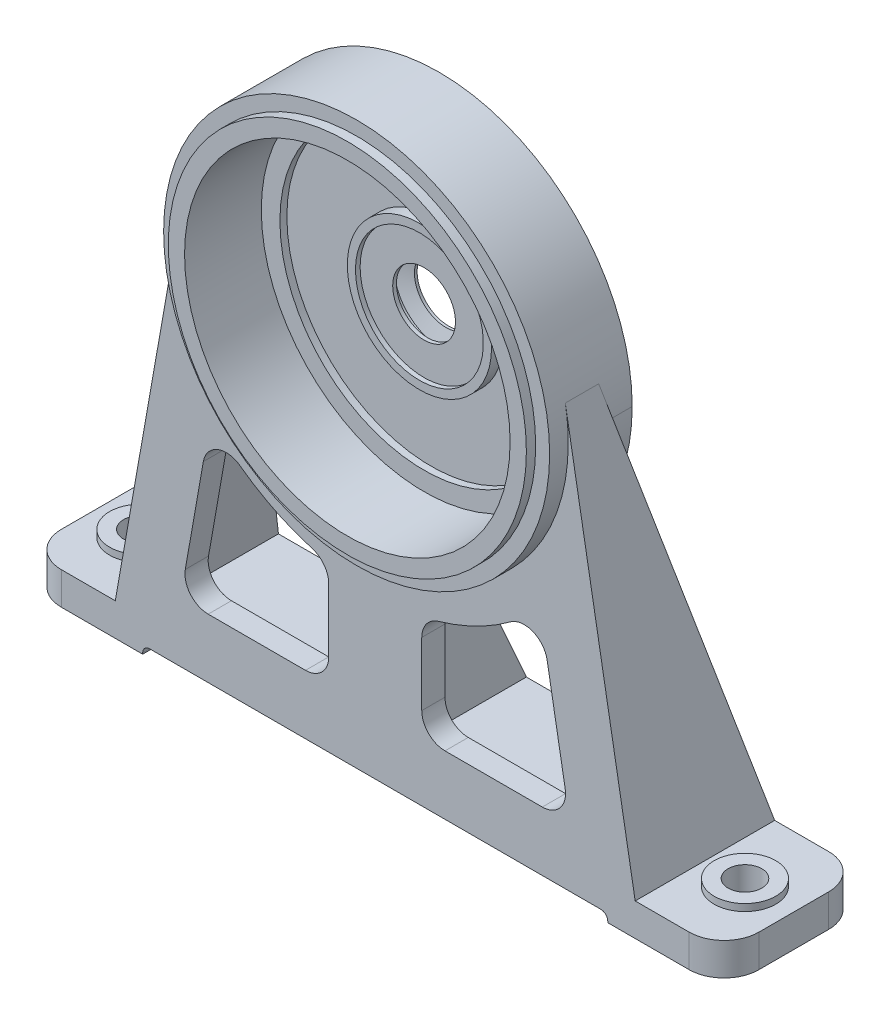
SolidWorks part; units mm, degrees
ref_plane "前视基准面" through (0, 0, 0) normal (0, 0, 1) x (1, 0, 0)
ref_plane "上视基准面" through (0, 0, 0) normal (0, 1, 0) x (1, 0, 0)
ref_plane "右视基准面" through (0, 0, 0) normal (1, 0, 0) x (0, 0, -1)
sketch "草图1" plane through (0, 0, 0) normal (0, 0, 1) x (1, 0, 0)
  circle A0 centre (0, 0) radius 83
  dimension "D1" = 166
extrude "凸台-拉伸1" add sketch "草图1" against normal blind 39.5
sketch "草图3" plane through (0, 0, 0) normal (0, 0, 1) x (1, 0, 0)
  circle A0 centre (0, 0) radius 34.5
  dimension "D1" = 69
extrude "凸台-拉伸2" add sketch "草图3" against normal blind 43.5
sketch "草图4" plane through (0, 0, 0) normal (0, 0, 1) x (1, 0, 0)
  circle A0 centre (0, 0) radius 77
  dimension "D1" = 154
extrude "切除-拉伸1" cut sketch "草图4" against normal blind 4 flip side to cut
sketch "草图5" plane through (0, 0, 0) normal (0, 1, 0) x (1, 0, 0)
  line L0 (0, -23.925) -> (0, 23.925) construction
  line L1 (150, 72) -> (-150, 72)
  line L2 (150, 72) -> (150, 12)
  line L3 (150, 12) -> (-150, 12)
  line L4 (-150, 72) -> (-150, 12)
  line L5 (150, 72) -> (-150, 12) construction
  line L6 (150, 12) -> (-150, 72) construction
  line L7 (-83, 4) -> (83, 4) construction
  point P0 (0, 42)
  point P7 (0, 0)
  point P8 (0, 0)
  point P9 (0, 0)
  dimension "D1" = 300
  dimension "D2" = 60
  dimension "D3" = 8
extrude "凸台-拉伸3" add sketch "草图5" along normal blind 14 from offset 170 separate body offset against normal yes
fillet "圆角1" radius 15 4 edges at (-150, -163, -72) (150, -163, -12) (-150, -163, -12) (150, -163, -72)
sketch "草图6" plane through (0, 0, -72) normal (0, 0, -1) x (-1, 0, 0)
  line L0 (-100, -170) -> (100, -170)
  line L1 (-135, -170) -> (135, -170) construction
  line L2 (0, 39.6) -> (0, -39.6) construction
  point P0 (0, 0)
  point P5 (0, -170)
  dimension "D1" = 200
extrude "切除-拉伸-薄壁1" cut sketch "草图6" against normal through all and the other way through all thin thin type one direction reverse wall 3.5
fillet "圆角2" radius 3 2 edges at (-100, -166.5, -42) (100, -166.5, -42)
sketch "草图7" plane through (0, 0, 0) normal (1, 0, 0) x (0, 0, -1)
  line L0 (72, -156) -> (48.0795, -66.7276)
  line L1 (39.5, -83) -> (39.5, 83) construction
  dimension "D1" = 15
surface "曲面-拉伸1" sketch "草图7" parameters "D1"=14
sketch "草图8" plane through (0, 0, -12) normal (0, 0, 1) x (1, 0, 0)
  line L0 (-81.739, 14.4128) -> (-111.7874, -156)
  line L1 (-135, -156) -> (135, -156) construction
  line L2 (0, 0) -> (0, -226.6041) construction
  line L3 (0, -39.6) -> (0, 39.6) construction
  line L4 (81.739, 14.4128) -> (111.7874, -156)
  line L5 (-111.7874, -156) -> (111.7874, -156)
  line L6 (-135, -156) -> (-111.7874, -156) construction
  line L7 (111.7874, -156) -> (135, -156) construction
  circle A0 centre (0, 0) radius 83 construction
  arc A1 (-81.739, 14.4128) -> (81.739, 14.4128) centre (0, 0) ccw
  arc A2 (81.739, 14.4128) -> (-81.739, 14.4128) centre (0, 0) ccw construction
  dimension "D1" = 100
extrude "凸台-拉伸4" add sketch "草图8" against normal up to surface (14.338 mm away)
sketch "草图9" plane through (0, 0, -72) normal (0, 0, -1) x (-1, 0, 0)
  line L15 (111.7874, -156) -> (-111.7874, -156) construction
  line L16 (101.6332, -156) -> (-101.6332, -156)
  line L17 (-101.6332, -156) -> (-111.7874, -156) construction
  line L18 (-81.8965, -44.0678) -> (-99.8699, -146)
  line L19 (-99.8699, -146) -> (99.8699, -146)
  line L20 (99.8699, -146) -> (81.8965, -44.0678)
  line L21 (-78.7495, -26.2205) -> (-101.6332, -156)
  line L22 (-99.8699, -146) -> (99.8699, -146) construction
  line L23 (101.6332, -156) -> (78.7495, -26.2205)
  line L24 (111.7874, -156) -> (101.6332, -156) construction
  arc A3 (78.7495, -26.2205) -> (-78.7495, -26.2205) centre (0, 0) ccw construction
  arc A4 (-78.7495, -26.2205) -> (-75.3945, -34.7083) centre (0, 0) ccw
  arc A5 (-75.3945, -34.7083) -> (75.3945, -34.7083) centre (0, 0) ccw
  arc A6 (-81.8965, -44.0678) -> (81.8965, -44.0678) centre (0, 0) ccw
  arc A7 (-81.8965, -44.0678) -> (81.8965, -44.0678) centre (0, 0) ccw construction
  arc A8 (75.3945, -34.7083) -> (-75.3945, -34.7083) centre (0, 0) ccw
  arc A9 (-75.3945, -34.7083) -> (75.3945, -34.7083) centre (0, 0) ccw
  arc A10 (75.3945, -34.7083) -> (78.7495, -26.2205) centre (0, 0) ccw
  dimension "D1" = 10
  dimension "D2" = 0
extrude "切除-拉伸2" cut sketch "草图9" against normal offset from surface (50 mm away) 10 up to face at (0, -145.9532, -12)
sketch "草图11" plane through (0, 0, 0) normal (1, 0, 0) x (0, 0, -1)
  line L0 (39.5, -83) -> (72, -156)
  line L1 (39.5, -83) -> (39.5, 83) construction
  point P5 (72, -156)
  point P6 (39.5, -93.4448)
  point P7 (39.5, -83)
rib "筋1" sketch "草图11" sketch "草图11" thickness 10 extrusion direction parallel to sketch draft on no parameters "D1"=10
sketch "草图12" plane through (0, 0, -22) normal (0, 0, -1) x (-1, 0, 0)
  line L6 (20, -95.9375) -> (20, -141)
  line L7 (20, -141) -> (83.7568, -141)
  line L8 (83.7568, -141) -> (70.836, -67.722)
  line L9 (20, -103.7497) -> (20, -131)
  line L10 (30, -141) -> (71.8393, -141)
  line L11 (81.6874, -129.2635) -> (73.9188, -85.2057)
  arc A1 (73.9188, -85.2057) -> (58.1383, -78.892) centre (64.0707, -86.9422) ccw
  arc A2 (20, -95.9375) -> (70.836, -67.722) centre (0, 0) ccw
  arc A3 (27.2222, -94.1432) -> (58.1383, -78.892) centre (0, 0) ccw
  arc A4 (71.8393, -141) -> (81.6874, -129.2635) centre (71.8393, -131) ccw
  arc A5 (20, -131) -> (30, -141) centre (30, -131) ccw
  arc A6 (20, -103.7497) -> (27.2222, -94.1432) centre (30, -103.7497) cw
  dimension "D2" = 10
  dimension "D1" = 15
extrude "切除-拉伸3" cut sketch "草图12" against normal through all both and the other way through all
mirror "镜向1" about plane through (0, 0, 0) normal (1, 0, 0) of "切除-拉伸3"
sketch "草图13" plane through (0, -156, 0) normal (0, 1, 0) x (1, 0, 0)
  line L0 (-135, 12) -> (-111.7874, 12) construction
  line L1 (0, -39.6) -> (0, 39.6) construction
  circle A0 centre (-130, 41) radius 13.25
  dimension "D1" = 26.5
  dimension "D2" = 29
  dimension "D3" = 130
extrude "凸台-拉伸5" add sketch "草图13" along normal blind 3
sketch "草图14" plane through (0, -153, 0) normal (0, 1, 0) x (1, 0, 0)
  circle A0 centre (-130, 41) radius 7.25
  dimension "D1" = 14.5
extrude "切除-拉伸4" cut sketch "草图14" against normal through all both and the other way through all
mirror "镜向2" about plane through (0, 0, 0) normal (1, 0, 0) of "切除-拉伸4", "凸台-拉伸5"
sketch "草图15" plane through (0, 0, 0) normal (0, 0, 1) x (1, 0, 0)
  circle A0 centre (0, 0) radius 70
  dimension "D1" = 140
extrude "切除-拉伸5" cut sketch "草图15" against normal blind 33 and the other way through all
sketch "草图16" plane through (0, 0, -33) normal (0, 0, 1) x (1, 0, 0)
  circle A0 centre (0, 0) radius 62
  dimension "D1" = 124
extrude "切除-拉伸6" cut sketch "草图16" against normal blind 3
sketch "草图17" plane through (0, 0, -36) normal (0, 0, 1) x (1, 0, 0)
  circle A0 centre (0, 0) radius 31
  dimension "D1" = 62
extrude "凸台-拉伸6" add sketch "草图17" along normal offset from surface (5 mm away) 2 up to face at (62, 0, -33) offset beyond the face yes
sketch "草图18" plane through (0, 0, 0) normal (1, 0, 0) x (0, 0, -1)
  line L0 (31, 0) -> (31, 27.5)
  line L1 (31, 31) -> (31, -31) construction
  line L2 (31, 27.5) -> (33, 27.5)
  line L3 (33, 27.5) -> (33, 13.5)
  line L4 (33, 13.5) -> (34.6244, 13.5)
  line L5 (34.6244, 13.5) -> (36.5, 20.5)
  line L7 (36.5, 20.5) -> (40.5, 20.5)
  line L8 (40.5, 20.5) -> (42.3756, 13.5)
  line L9 (42.3756, 13.5) -> (43.5, 13.5)
  line L10 (43.5, -34.5) -> (43.5, 34.5) construction
  line L11 (43.5, 13.5) -> (43.5, 0)
  line L12 (43.5, 0) -> (31, 0) construction
  line L13 (31, 0) -> (43.5, 0)
  point P4 (0, 0)
  point P9 (38.5, 20.5)
  dimension "D1" = 27
  dimension "D2" = 41
  dimension "D3" = 55
  dimension "D4" = 2
  dimension "D5" = 4
  dimension "D6" = 30
  dimension "D7" = 5
revolve "切除-旋转1" cut sketch "草图18" angle 360 about L12
